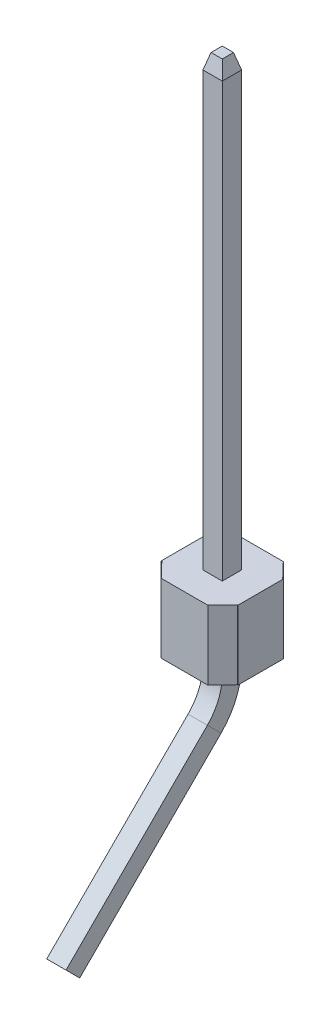
SolidWorks part; units mm, degrees
ref_plane "Front Plane" through (0, 0, 0) normal (0, 0, 1) x (1, 0, 0)
ref_plane "Top Plane" through (0, 0, 0) normal (0, 1, 0) x (1, 0, 0)
ref_plane "Right Plane" through (0, 0, 0) normal (1, 0, 0) x (0, 0, -1)
sketch "Sketch1" plane through (0, 0, 0) normal (0, 1, 0) x (1, 0, 0)
  line L14 (-0.77, 1.25) -> (0.77, 1.25)
  line L20 (-0.77, -1.25) -> (0.77, -1.25)
  line L22 (1.27, -0.75) -> (1.27, 0.75)
  line L23 (1.27, -1.25) -> (-1.27, 1.25) construction
  line L24 (0.77, -1.25) -> (1.25, -0.75)
  line L25 (1.25, -0.75) -> (1.27, -0.75)
  line L26 (0, 0) -> (0, -1.4708) construction
  line L27 (0, 0) -> (1.4893, 0) construction
  line L28 (0.77, 1.25) -> (1.25, 0.75)
  line L29 (1.25, 0.75) -> (1.27, 0.75)
  line L30 (-1.25, 0.75) -> (-1.27, 0.75)
  line L31 (-0.77, 1.25) -> (-1.25, 0.75)
  line L32 (-1.25, -0.75) -> (-1.27, -0.75)
  line L33 (-0.77, -1.25) -> (-1.25, -0.75)
  line L34 (-1.27, -0.75) -> (-1.27, 0.75)
  point P18 (0, 0)
  point P20 (0, 0)
  point P21 (0, 0)
  point P22 (0, 0)
  point P25 (0, 1.25)
  point P29 (0, 0)
  point P38 (1.27, 0)
  point P43 (0, -1.25)
  dimension "D11" = 1.25
  dimension "D12" = 1.27
  dimension "D13" = 0.5
  dimension "D14" = 0.02
  dimension "D15" = 0.5
extrude "Boss-Extrude1" add sketch "Sketch1" along normal blind 2.29
sketch "Sketch2" plane through (0, 0, 0) normal (1, 0, 0) x (0, 0, -1)
  line L0 (0, 17.12) -> (0, -0.4081)
  line L2 (-0.5858, -1.8224) -> (-5.2634, -6.5)
  line L3 (0.75, 0) -> (1.25, 0) construction
  arc A0 (0, -0.4081) -> (-0.5858, -1.8224) centre (-2, -0.4081) cw
  dimension "D4" = 2
  dimension "D1" = 23.62
  dimension "D2" = 135
  dimension "D3" = 6.5
ref_plane "Plane1" through (0, 17.12, 0) normal (0, 1, 0) x (1, 0, 0)
sketch "Sketch3" plane through (0, 17.12, 0) normal (0, 1, 0) x (1, 0, 0)
  line L1 (-0.32, 0.32) -> (0.32, 0.32)
  line L2 (-0.32, 0.32) -> (-0.32, -0.32)
  line L3 (-0.32, -0.32) -> (0.32, -0.32)
  line L4 (0.32, 0.32) -> (0.32, -0.32)
  line L5 (-0.32, 0.32) -> (0.32, -0.32) construction
  line L6 (-0.32, -0.32) -> (0.32, 0.32) construction
  point P0 (0, 0)
  dimension "D1" = 0.64
sweep "Sweep1" add profiles "Sketch3" path "Sketch2"
chamfer "Chamfer3" distance 0.5 angle 15 4 edges at (0, 17.12, 0.32) (-0.32, 17.12, 0) (0, 17.12, -0.32) (0.32, 17.12, 0)
